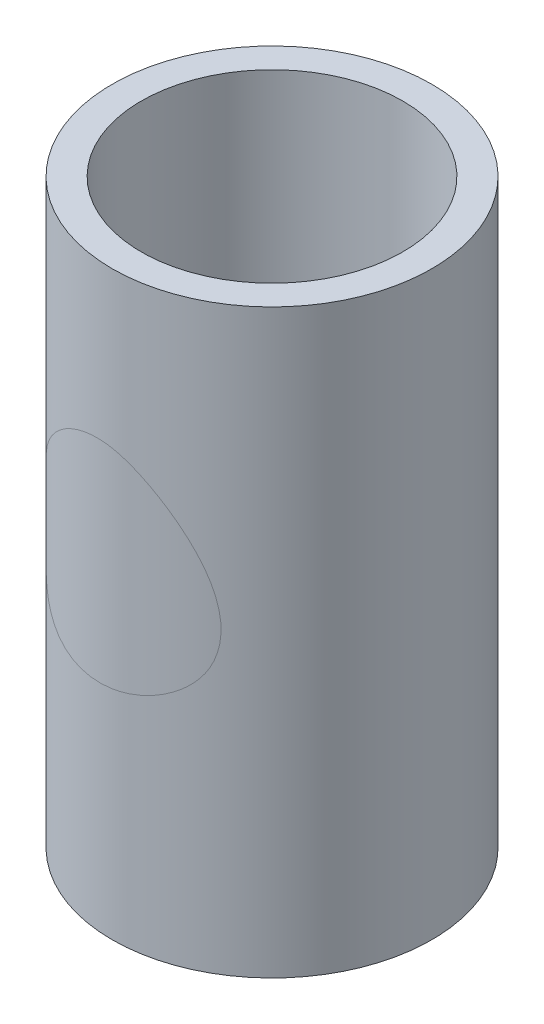
SolidWorks part; units mm, degrees
ref_plane "Спереди" through (0, 0, 0) normal (0, 0, 1) x (1, 0, 0)
ref_plane "Сверху" through (0, 0, 0) normal (0, 1, 0) x (1, 0, 0)
ref_plane "Справа" through (0, 0, 0) normal (1, 0, 0) x (0, 0, -1)
sketch "Эскиз1" plane through (0, 0, 0) normal (0, 0, 1) x (1, 0, 0)
  line L0 (0, -110.6031) -> (0, 130.0787) construction
  line L1 (45, 100) -> (55, 100)
  line L2 (45, 100) -> (45, -100)
  line L3 (45, -100) -> (55, -100)
  line L4 (55, 100) -> (55, -100)
  point P4 (45, 0)
  dimension "D1" = 10
  dimension "D2" = 200
  dimension "D3" = 45
revolve "Повернуть1" add sketch "Эскиз1" angle 360 about L0
ref_plane "Плоскость1" through (0, 0, 55) normal (0, 0, 1) x (1, 0, 0)
sketch "Эскиз2" plane through (0, 0, 55) normal (0, 0, 1) x (1, 0, 0)
  spline S0 degree 3 poles (-54.6404, -30.9953) (-37.7126, 28.6116) (8.4641, 64.6749) (54.8948, -29.3483) (-54.6404, -30.9953) (-37.7126, 28.6116) (8.4641, 64.6749) knots -0.813776 -0.511938 -0.19742 0 0.186224 0.488062 0.80258 1 1.186224 1.488062 1.80258 only from (-33.0608, 26.2387) to (-33.0608, 26.2387)
split line "Разделяющая линия1"
